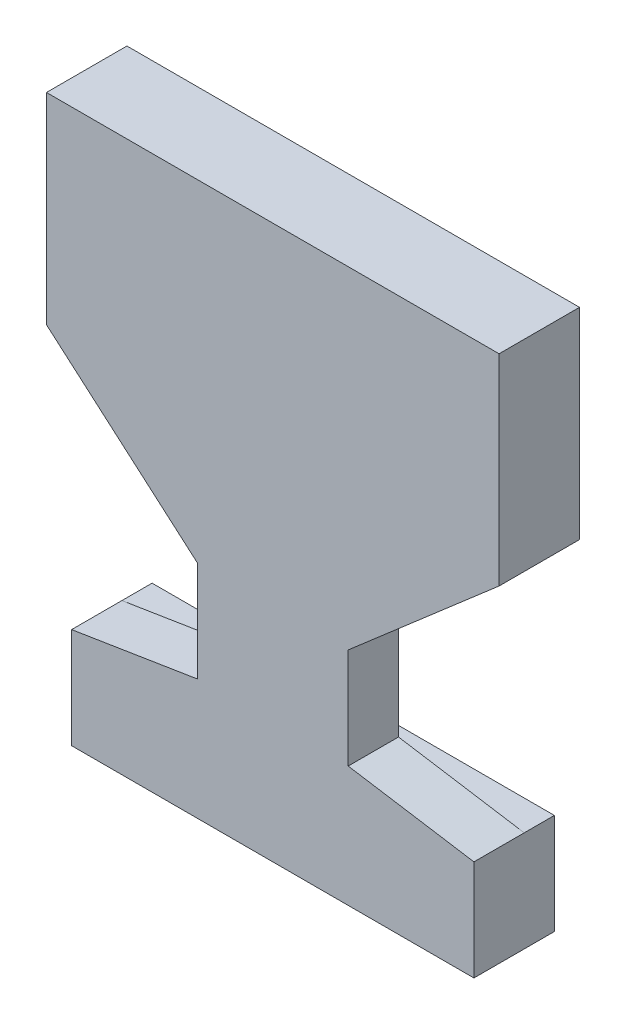
SolidWorks part; units mm, degrees
ref_plane "Спереди" through (0, 0, 0) normal (0, 0, 1) x (1, 0, 0)
ref_plane "Сверху" through (0, 0, 0) normal (0, 1, 0) x (1, 0, 0)
ref_plane "Справа" through (0, 0, 0) normal (1, 0, 0) x (0, 0, -1)
sketch "Эскиз2" plane through (0, 0, 0) normal (0, 0, 1) x (1, 0, 0)
  line L0 (0, 0) -> (40, 0)
  line L1 (40, 0) -> (40, 10)
  line L2 (40, 10) -> (27.5, 12)
  line L3 (27.5, 12) -> (27.5, 22)
  line L4 (27.5, 22) -> (42.5, 35)
  line L5 (42.5, 35) -> (42.5, 55)
  line L6 (42.5, 55) -> (-2.5, 55)
  line L7 (-2.5, 55) -> (-2.5, 35)
  line L8 (-2.5, 35) -> (12.5, 22)
  line L9 (12.5, 22) -> (12.5, 12)
  line L10 (12.5, 12) -> (0, 10)
  line L11 (0, 10) -> (0, 0)
  dimension "D1" = 45
  dimension "D2" = 40
  dimension "D3" = 15
  dimension "D4" = 12.5
  dimension "D5" = 10
  dimension "D6" = 12
  dimension "D7" = 55
  dimension "D8" = 10
  dimension "D9" = 2.5
  dimension "D10" = 20
extrude "Бобышка-Вытянуть1" add sketch "Эскиз2" along normal blind 8
sketch "Эскиз3" plane through (0, 0, 0) normal (0, 0, -1) x (-1, 0, 0)
  line L0 (-40, 10) -> (-27.5, 12) construction
  line L1 (-27.5, 12) -> (-27.5, 22) construction
  line L2 (-27.5, 22) -> (-42.5, 35) construction
  line L3 (2.5, 35) -> (-12.5, 22) construction
  line L4 (-12.5, 22) -> (-12.5, 12) construction
  line L5 (-12.5, 12) -> (0, 10) construction
  line L6 (-40, 10) -> (-27.5, 12)
  line L7 (-27.5, 12) -> (-27.5, 22)
  line L8 (-27.5, 22) -> (-42.5, 35)
  line L9 (2.5, 35) -> (-12.5, 22)
  line L10 (-12.5, 22) -> (-12.5, 12)
  line L11 (-12.5, 12) -> (0, 10)
  line L12 (-42.5, 35) -> (2.5, 35)
  line L13 (-40, 10) -> (0, 10)
extrude "Вырез-Вытянуть1" cut sketch "Эскиз3" against normal blind 3
